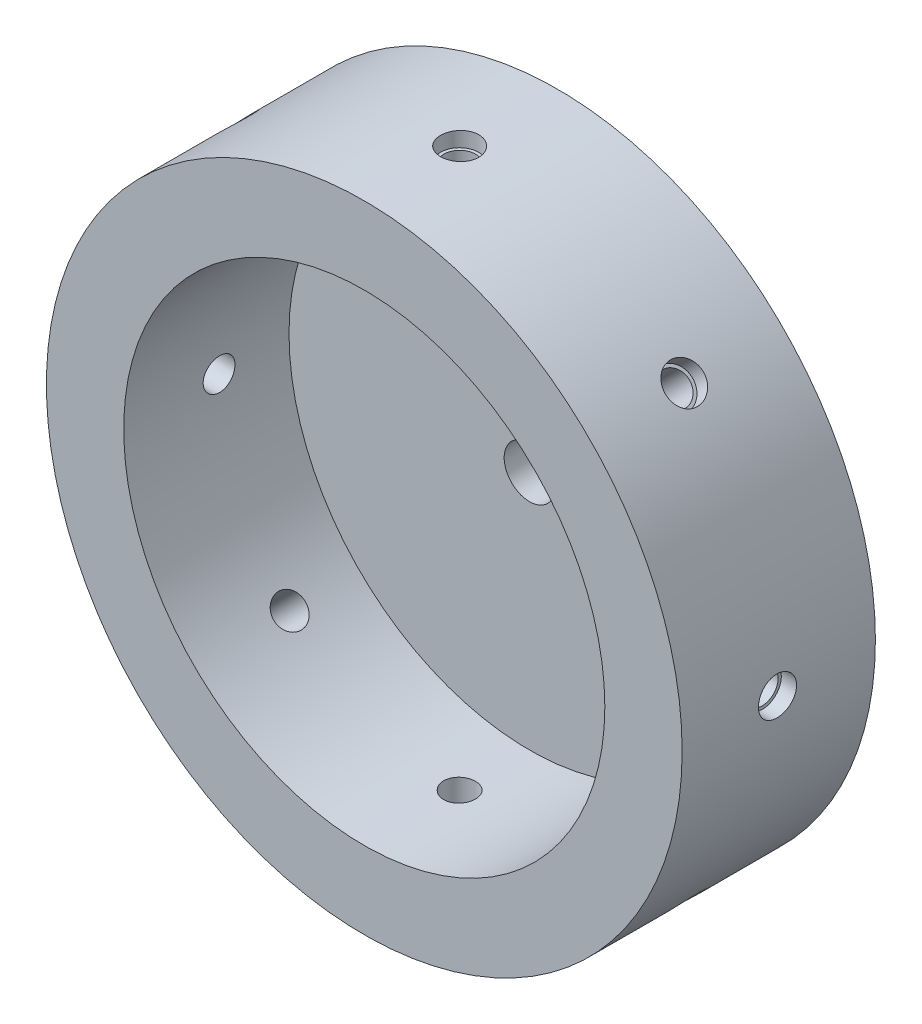
SolidWorks part; units mm, degrees
other "Markup1"
sketch "Sketch8" plane through (110, 110, 0) normal (0.0901, 0.1911, 0.9774) x (0.9758, -0.2132, -0.0483)
ref_plane "Front Plane" through (0, 0, 0) normal (0, 0, 1) x (1, 0, 0)
ref_plane "Top Plane" through (0, 0, 0) normal (0, 1, 0) x (1, 0, 0)
ref_plane "Right Plane" through (0, 0, 0) normal (1, 0, 0) x (0, 0, -1)
sketch "Sketch2" plane through (0, 0, 0) normal (0, 0, 1) x (1, 0, 0)
  circle A0 centre (0, 0) radius 125
  circle A1 centre (0, 0) radius 94.6
  dimension "D1" = 250
  dimension "D2" = 189.2
extrude "Boss-Extrude1" add sketch "Sketch2" against normal blind 75
sketch "Sketch3" plane through (0, 0, -75) normal (0, 0, -1) x (-1, 0, 0)
  circle A0 centre (0, 0) radius 125
  circle A1 centre (0, 0) radius 10
  dimension "D1" = 20
  dimension "D2" = 250
extrude "Boss-Extrude2" add sketch "Sketch3" along normal blind 1 and the other way blind 10
ref_plane "Plane1" through (0, -125, 0) normal (0, 1, 0) x (1, 0, 0)
sketch "Sketch4" plane through (0, -125, 0) normal (0, 1, 0) x (1, 0, 0)
  circle A0 centre (0, 37.5) radius 7.5
extrude "Cut-Extrude4" cut sketch "Sketch4" along normal blind 6
sketch "Sketch7" plane through (0, -119, 0) normal (0, -1, 0) x (1, 0, 0)
  circle A0 centre (0, -37.5) radius 6.25
extrude "Cut-Extrude5" cut sketch "Sketch7" against normal blind 50
pattern_circular "CirPattern1" count 8 over 360 about axis through (0, 0, 0) along (0, 0, 1) of "Cut-Extrude5", "Cut-Extrude4"
